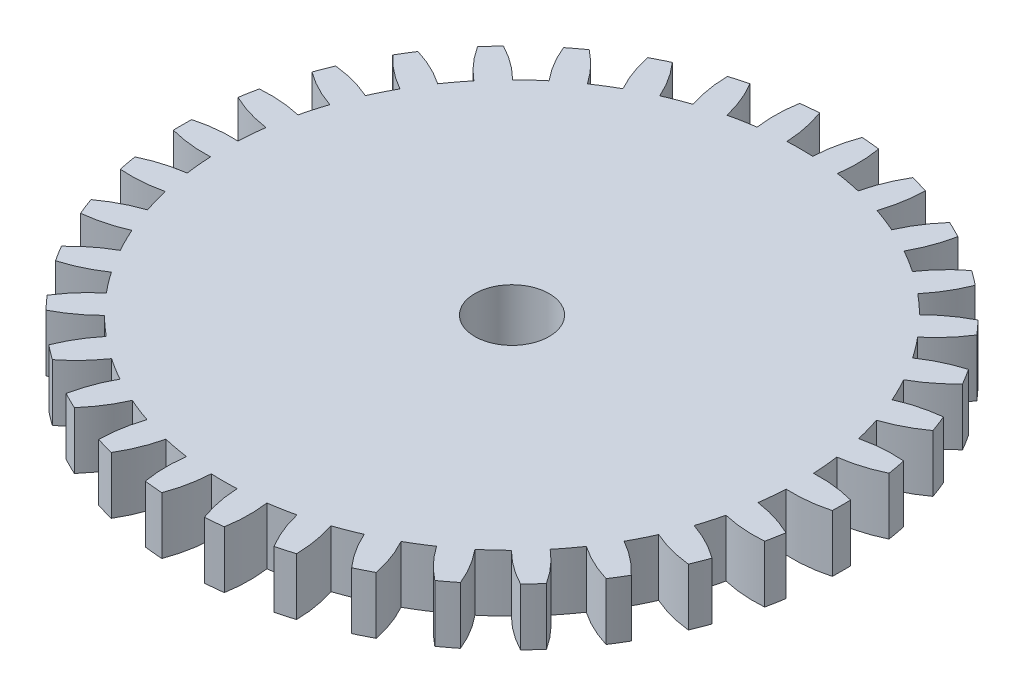
SolidWorks part; units mm, degrees
ref_plane "Front Plane" through (0, 0, 0) normal (0, 0, 1) x (1, 0, 0)
ref_plane "Top Plane" through (0, 0, 0) normal (0, 1, 0) x (1, 0, 0)
ref_plane "Right Plane" through (0, 0, 0) normal (1, 0, 0) x (0, 0, -1)
sketch "Sketch1" plane through (0, 0, 0) normal (0, 1, 0) x (1, 0, 0)
  circle A0 centre (0, 0) radius 13.5001
  dimension "D1" = 27.0002
extrude "Boss-Extrude1" add sketch "Sketch1" along normal blind 2.3368 contours A0
sketch "Sketch2" plane through (0, 2.3368, 0) normal (0, 1, 0) x (1, 0, 0)
  line L0 (0, 0) -> (0, 18.3647) construction
  line L1 (1.1173, 14.0322) -> (-1.1173, 14.0322)
  line L2 (0, 0) -> (0.8213, 18.322) construction
  circle A0 centre (0, 0) radius 12.7508 construction
  arc A1 (0.5285, 11.7899) -> (-0.5285, 11.7899) centre (0, 0) ccw
  arc A4 (0.5285, 11.7899) -> (1.1173, 14.0322) centre (6.0317, 11.5432) cw
  arc A5 (-0.5285, 11.7899) -> (-1.1173, 14.0322) centre (-6.0317, 11.5432) ccw
  point P13 (0, 14.0322)
  dimension "D2" = 2.567
extrude "Cut-Extrude1" cut sketch "Sketch2" against normal blind 2.3368
sketch "Sketch3" plane through (0, 0, 0) normal (0, 1, 0) x (1, 0, 0)
  circle A0 centre (0, 0) radius 1.524
  dimension "D1" = 3.048
extrude "Cut-Extrude2" cut sketch "Sketch3" along normal blind 2.3368 contours A0
pattern_circular "CirPattern1" count 34 over 360 about axis through (0, 0, 0) along (0, 1, 0) of "Cut-Extrude1"
